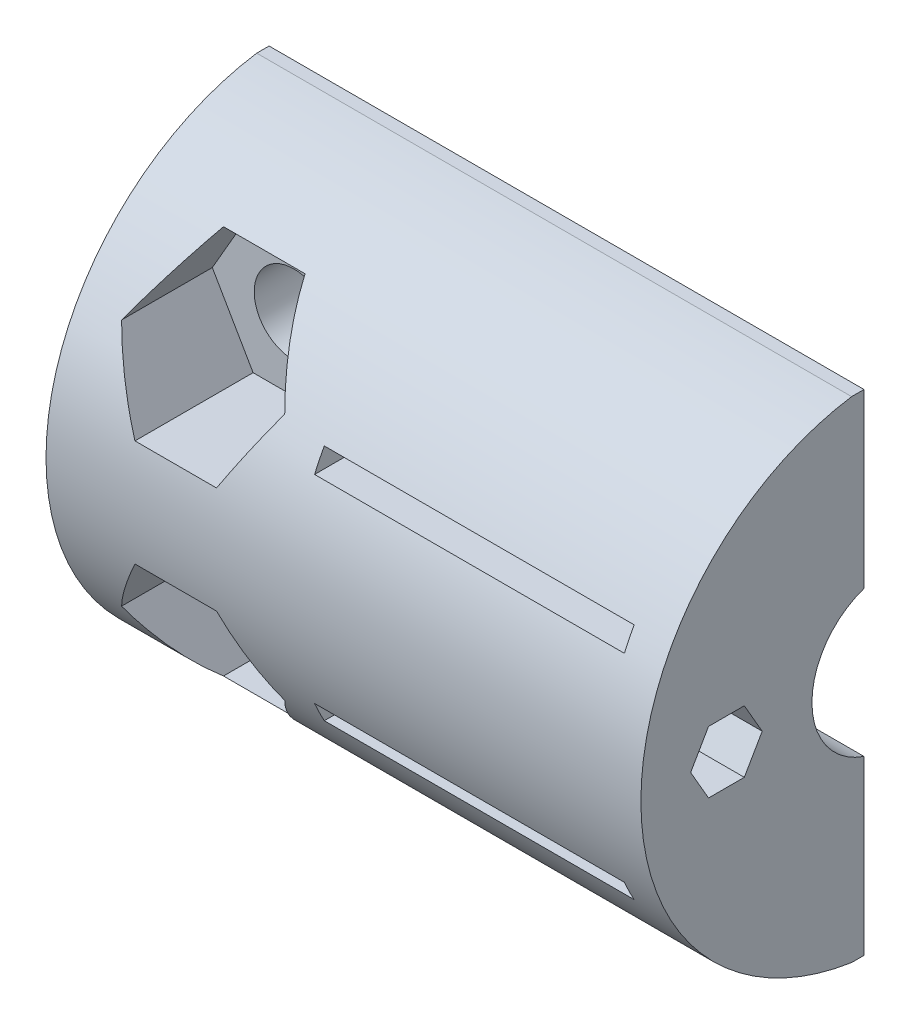
SolidWorks part; units mm, degrees
ref_plane "xy" through (0, 0, 0) normal (0, 0, 1) x (1, 0, 0)
ref_plane "xz" through (0, 0, 0) normal (0, 1, 0) x (1, 0, 0)
ref_plane "yz" through (0, 0, 0) normal (1, 0, 0) x (0, 0, -1)
sketch "Skizze1" plane through (0, 0, 0) normal (1, 0, 0) x (0, 0, -1)
  line L0 (-1.5, 9.8869) -> (-1, 9.8869)
  line L1 (-1, 9.8869) -> (-1, 2.9343)
  line L2 (-1, -9.8869) -> (-1.5, -9.8869)
  line L3 (-1, -2.9343) -> (-1, -9.8869)
  arc A0 (-1.5, -9.8869) -> (-1.5, 9.8869) centre (0, 0) cw
  arc A1 (-1, 2.9343) -> (-1, -2.9343) centre (0, 0) ccw
  dimension "D3" = 6.2
  dimension "D4" = 10
  dimension "D1" = 1
  dimension "D2" = 0.5
extrude "Aufsatz-Linear austragen1" add sketch "Skizze1" along normal blind 14 and the other way blind 10
sketch "Skizze2" plane through (0, 0, 0) normal (0, 0, 1) x (1, 0, 0)
  line L1 (0, 4.8) -> (12.5, 4.8)
  line L2 (0, 4.8) -> (0, 4)
  line L3 (0, 4) -> (12.5, 4)
  line L4 (12.5, 4.8) -> (12.5, 4)
  dimension "D1" = 0.8
  dimension "D2" = 4
  dimension "D3" = 12.5
extrude "Schnitt-Linear austragen1" cut sketch "Skizze2" along normal through all
sketch "Skizze3" plane through (0, 0, 0) normal (0, 0, 1) x (1, 0, 0)
  line L1 (-3.3546, 2.15) -> (-1.7091, 5)
  line L2 (-1.7091, 5) -> (-3.3546, 7.85)
  line L3 (-3.3546, 7.85) -> (-6.6454, 7.85)
  line L4 (-6.6454, 7.85) -> (-8.2909, 5)
  line L5 (-8.2909, 5) -> (-6.6454, 2.15)
  line L6 (-6.6454, 2.15) -> (-3.3546, 2.15)
  circle A0 centre (-5, 5) radius 2.85 construction
  dimension "D1" = 5.7
  dimension "D2" = 5
  dimension "D3" = 5
extrude "Schnitt-Linear austragen2" cut sketch "Skizze3" along normal through all from offset 5
sketch "Skizze4" plane through (0, 0, 0) normal (0, 0, 1) x (1, 0, 0)
  circle A0 centre (-5, 5) radius 1.6
  dimension "D1" = 3.2
extrude "Schnitt-Linear austragen3" cut sketch "Skizze4" along normal through all
mirror "Spiegeln1" about plane through (0, 0, 0) normal (0, 1, 0) of "Schnitt-Linear austragen3", "Schnitt-Linear austragen1", "Schnitt-Linear austragen2"
sketch "Skizze6" plane through (0, 0, 0) normal (1, 0, 0) x (0, 0, -1)
  line L0 (-10, 0) -> (-3.1, 0) construction
  line L1 (-5.8283, 1.25) -> (-7.2717, 1.25)
  line L2 (-7.2717, 1.25) -> (-7.9934, 0)
  line L3 (-7.9934, 0) -> (-7.2717, -1.25)
  line L4 (-7.2717, -1.25) -> (-5.8283, -1.25)
  line L5 (-5.8283, -1.25) -> (-5.1066, 0)
  line L6 (-5.1066, 0) -> (-5.8283, 1.25)
  circle A0 centre (-6.55, 0) radius 1.25 construction
  arc A1 (-1.5, 9.8869) -> (-1.5, -9.8869) centre (0, 0) ccw construction
  arc A2 (-1, 2.9343) -> (-1, -2.9343) centre (0, 0) ccw construction
  dimension "D1" = 2.5
extrude "Schnitt-Linear austragen4" cut sketch "Skizze6" against normal blind 10 from surface at 14 starting at face at (14, 0, 2.9333)
